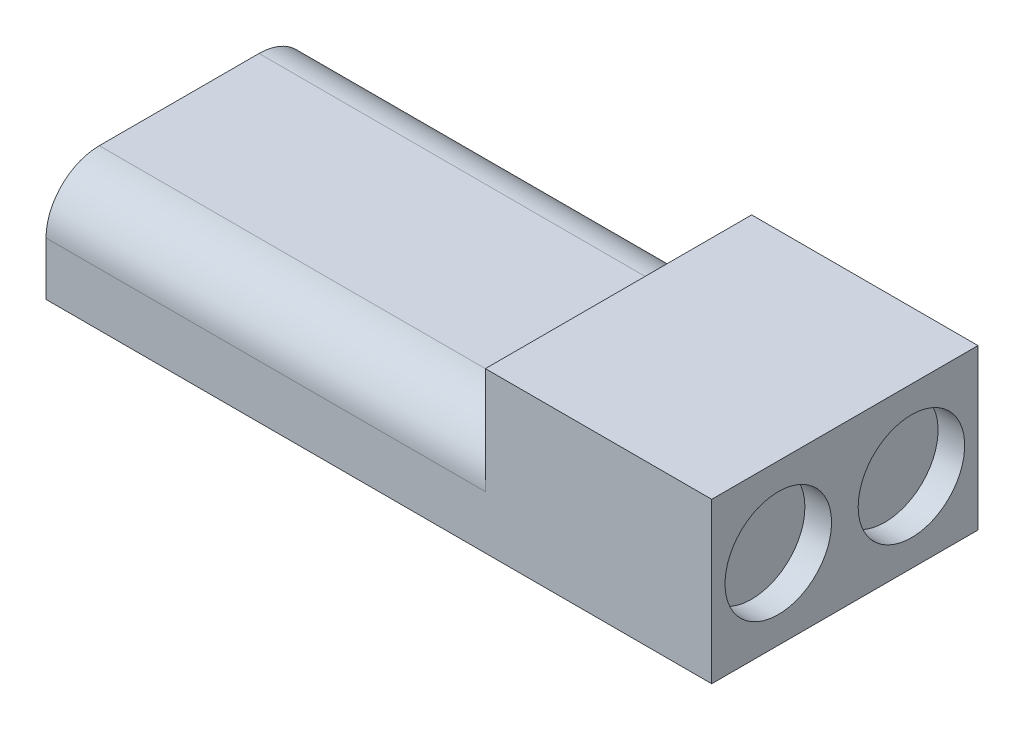
SolidWorks part; units mm, degrees
material "PVC 0.007 Plasticized"
ref_plane "Front Plane" through (0, 0, 0) normal (0, 0, 1) x (1, 0, 0)
ref_plane "Top Plane" through (0, 0, 0) normal (0, 1, 0) x (1, 0, 0)
ref_plane "Right Plane" through (0, 0, 0) normal (1, 0, 0) x (0, 0, -1)
sketch "Sketch1" plane through (0, 0, 0) normal (0, 0, 1) x (1, 0, 0)
  line L0 (10.4167, 3) -> (10.4167, 0)
  line L1 (-2.0833, 2) -> (6.1667, 2)
  line L2 (-2.0833, 2) -> (-2.0833, 0)
  line L3 (-2.0833, 0) -> (10.4167, 0)
  line L6 (6.1667, 2) -> (6.1667, 3)
  line L7 (6.1667, 3) -> (10.4167, 3)
  dimension "D1" = 12.5
  dimension "D2" = 4.25
  dimension "D3" = 2
  dimension "D4" = 3
extrude "Boss-Extrude1" add sketch "Sketch1" along normal blind 5
fillet "Fillet4" radius 1 2 edges at (2.0417, 2, 0) (2.0417, 2, 5)
sketch "Sketch2" plane through (-2.0833, 0, 0) normal (-1, 0, 0) x (0, 0, 1)
  line L0 (0.8222, 0.5) -> (1.6778, 0.5)
  line L1 (2.5, 0) -> (2.5, 3.3317)
  line L2 (5, 0) -> (0, 0) construction
  line L3 (4.1778, 0.5) -> (3.3222, 0.5)
  arc A0 (0.8222, 0.5) -> (1.6778, 0.5) centre (1.25, 0.5) cw
  arc A1 (4.1778, 0.5) -> (3.3222, 0.5) centre (3.75, 0.5) ccw
  point P10 (0, 0)
  point P11 (0, 0)
  point P12 (0, 0)
  point P13 (0, 0)
  dimension "D2" = 1.25
  dimension "D1" = 0.5
extrude "Cut-Extrude3" cut sketch "Sketch2" against normal blind 10 contours L3 A1 | L0 A0
sketch "Sketch5" plane through (10.4167, 0, 0) normal (1, 0, 0) x (0, 0, -1)
  line L2 (-5, 0) -> (-5, 3) construction
  circle A1 centre (-3.75, 1.5) radius 1
  circle A2 centre (-1.25, 1.5) radius 1
  dimension "D1" = 2
  dimension "D2" = 1.25
  dimension "D3" = 2
extrude "Cut-Extrude4" cut sketch "Sketch5" against normal blind 0.5
